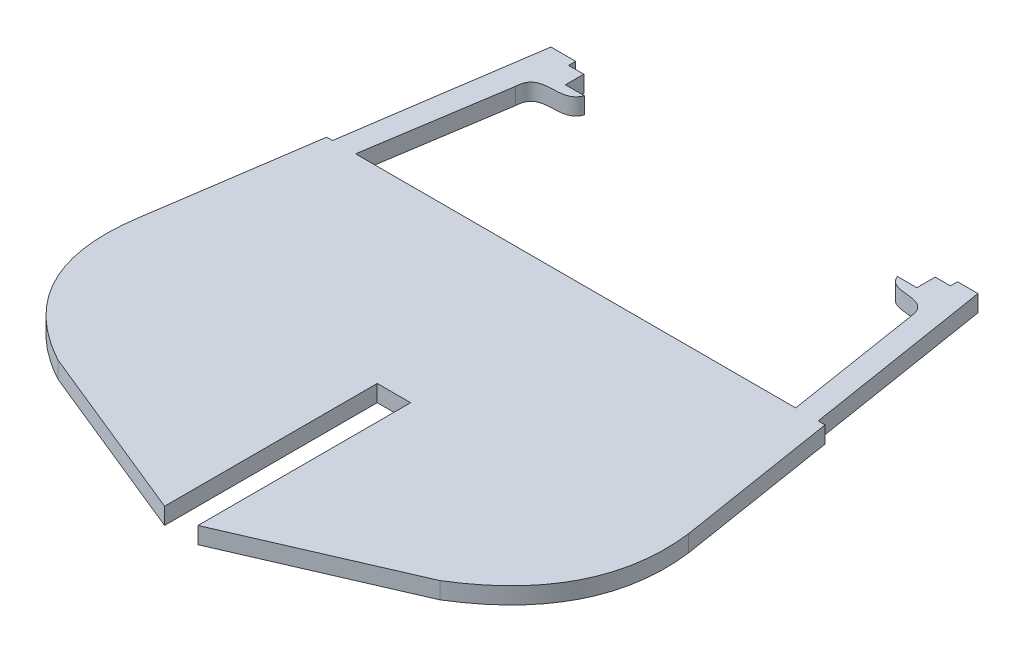
SolidWorks part; units mm, degrees
ref_plane "前视基准面" through (0, 0, 0) normal (0, 0, 1) x (1, 0, 0)
ref_plane "上视基准面" through (0, 0, 0) normal (0, 1, 0) x (1, 0, 0)
ref_plane "右视基准面" through (0, 0, 0) normal (1, 0, 0) x (0, 0, -1)
sketch "草图1" plane through (0, 0, 0) normal (0, 1, 0) x (1, 0, 0)
  line L0 (-171.9711, -45.599) -> (-166.1882, -6.6273)
  line L1 (-166.1882, -6.6273) -> (-164.8053, -6.6273)
  line L2 (-164.8053, -6.6273) -> (-158.0408, 38.9599)
  line L3 (-158.0408, 38.9599) -> (-152.1081, 38.9599)
  line L4 (-152.1081, 38.9599) -> (-152.1081, 37.2474)
  line L5 (-152.1081, 37.2474) -> (-148.4623, 37.2474)
  line L6 (-148.4623, 37.2474) -> (-148.4623, 32.8473)
  line L7 (-148.4623, 32.8473) -> (-143.9366, 32.8473)
  line L8 (-154.1195, 26.5616) -> (-159.2739, -6.6273)
  line L9 (-159.2739, -6.6273) -> (-53.7987, -6.6273)
  line L10 (-53.7987, -6.6273) -> (-59.0788, 26.5616)
  line L11 (-68.8846, 32.8473) -> (-64.2331, 32.8473)
  line L12 (-64.2331, 32.8473) -> (-64.2331, 37.2474)
  line L13 (-64.2331, 37.2474) -> (-60.5874, 37.2474)
  line L14 (-60.5874, 37.2474) -> (-60.5874, 38.9599)
  line L15 (-60.5874, 38.9599) -> (-55.6845, 38.9599)
  line L16 (-55.6845, 38.9599) -> (-48.393, -6.6273)
  line L17 (-48.393, -6.6273) -> (-46.7587, -6.6273)
  line L18 (-46.7587, -6.6273) -> (-40.5253, -45.599)
  line L19 (-152.1081, -85.0989) -> (-109.0246, -102.6516)
  line L20 (-109.0246, -102.6516) -> (-109.0246, -51.6897)
  line L21 (-109.0246, -51.6897) -> (-101.0246, -51.6897)
  line L22 (-101.0246, -51.6897) -> (-101.0246, -102.6516)
  line L23 (-101.0246, -102.6516) -> (-60.5874, -85.0989)
  spline S0 degree 3 poles (-143.9366, 32.8473) (-145.69, 27.9887) (-153.8626, 33.2348) (-154.1195, 26.5616) knots 0 0 0 0 1 1 1 1
  spline S1 degree 3 poles (-68.8846, 32.8473) (-67.1835, 28.2386) (-59.8753, 32.5565) (-59.0788, 26.5616) knots 0 0 0 0 1 1 1 1
  spline S2 degree 2 poles (-171.9711, -45.599) (-176.1659, -72.055) (-152.1081, -85.0989) knots 0 0 0 1 1 1
  spline S3 degree 2 poles (-40.5253, -45.599) (-37.3327, -70.8151) (-60.5874, -85.0989) knots 0 0 0 1 1 1
  dimension "D1" = 8
  dimension "D2" = 50.9619
extrude "凸台-拉伸1" add sketch "草图1" along normal blind 4
